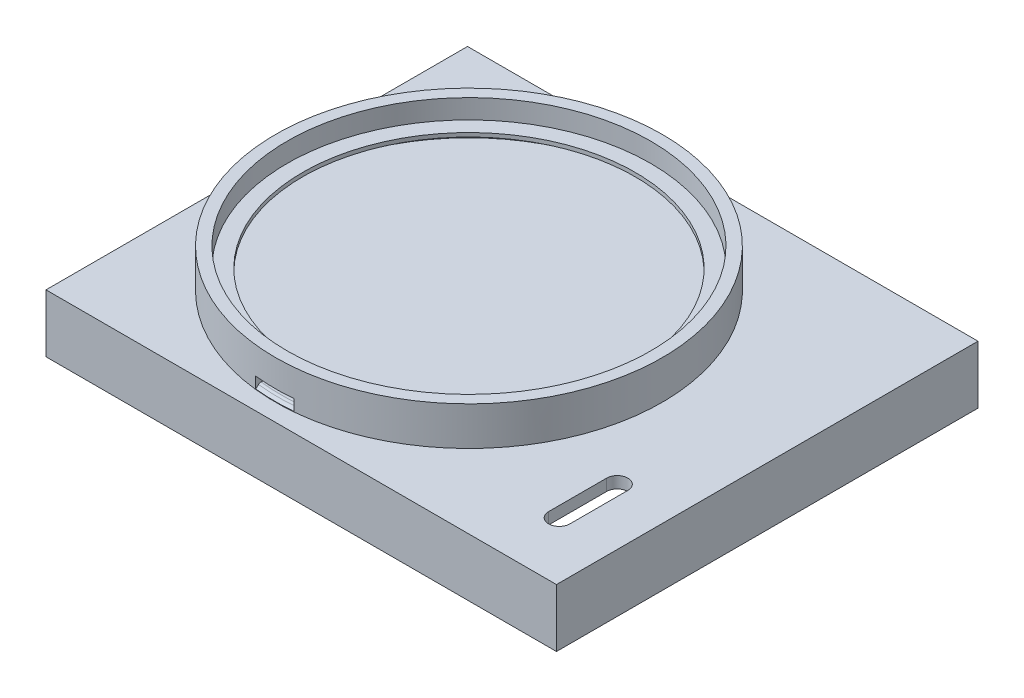
SolidWorks part; units mm, degrees
ref_plane "Front Plane" through (0, 0, 0) normal (0, 0, 1) x (1, 0, 0)
ref_plane "Top Plane" through (0, 0, 0) normal (0, 1, 0) x (1, 0, 0)
ref_plane "Right Plane" through (0, 0, 0) normal (1, 0, 0) x (0, 0, -1)
sketch "Sketch1" plane through (0, 0, 0) normal (0, 1, 0) x (1, 0, 0)
  line L1 (-66, -54.5) -> (66, -54.5)
  line L2 (-66, -54.5) -> (-66, 54.5)
  line L3 (-66, 54.5) -> (66, 54.5)
  line L4 (66, -54.5) -> (66, 54.5)
  line L5 (-66, -54.5) -> (66, 54.5) construction
  line L6 (-66, 54.5) -> (66, -54.5) construction
  point P0 (0, 0)
  dimension "D1" = 132
  dimension "D2" = 109
extrude "Boss-Extrude1" add sketch "Sketch1" along normal blind 15
sketch "Sketch2" plane through (0, 0, 0) normal (0, -1, 0) x (1, 0, 0)
  line L0 (-66, 54.5) -> (66, 54.5) construction
  line L1 (-63, -51.5) -> (63, -51.5)
  line L2 (-63, -51.5) -> (-63, 51.5)
  line L3 (-63, 51.5) -> (63, 51.5)
  line L4 (63, -51.5) -> (63, 51.5)
  line L5 (-63, -51.5) -> (63, 51.5) construction
  line L6 (-63, 51.5) -> (63, -51.5) construction
  line L7 (66, 54.5) -> (66, -54.5) construction
  point P0 (0, 0)
  dimension "D1" = 3
  dimension "D2" = 3
extrude "Cut-Extrude1" cut sketch "Sketch2" against normal blind 12
sketch "Sketch3" plane through (-63, 0, 0) normal (1, 0, 0) x (0, 0, -1)
  line L0 (-51.5, 0) -> (-51.5, 2) construction
  line L1 (-51.5, 0) -> (51.5, 0) construction
  line L2 (-51.5, 2) -> (51.5, 2) construction
  line L3 (51.5, 12) -> (51.5, 0) construction
  line L5 (-9, 1.25) -> (9, 1.25)
  line L6 (-9, 1.25) -> (-9, 2.75)
  line L7 (-9, 2.75) -> (9, 2.75)
  line L8 (9, 1.25) -> (9, 2.75)
  line L9 (-9, 1.25) -> (9, 2.75) construction
  line L10 (-9, 2.75) -> (9, 1.25) construction
  point P4 (0, 2)
  dimension "D1" = 2
  dimension "D2" = 18
  dimension "D3" = 1.5
sketch "Sketch6" plane through (63, 0, 0) normal (-1, 0, 0) x (0, 0, 1)
  line L0 (-51.5, 0) -> (-51.5, 2) construction
  line L1 (-51.5, 12) -> (-51.5, 0) construction
  line L2 (-51.5, 2) -> (51.5, 2) construction
  line L3 (51.5, 12) -> (51.5, 0) construction
  line L5 (-9, 2.75) -> (9, 2.75)
  line L6 (-9, 2.75) -> (-9, 1.25)
  line L7 (-9, 1.25) -> (9, 1.25)
  line L8 (9, 2.75) -> (9, 1.25)
  line L9 (-9, 2.75) -> (9, 1.25) construction
  line L10 (-9, 1.25) -> (9, 2.75) construction
  point P5 (0, 2)
  dimension "D1" = 2
  dimension "D2" = 18
  dimension "D3" = 1.5
extrude "Boss-Extrude6" add sketch "Sketch3" along normal blind 3
extrude "Boss-Extrude7" add sketch "Sketch6" along normal blind 3
sketch "Sketch14" plane through (0, 15, 0) normal (0, 1, 0) x (1, 0, 0)
  line L1 (48.6464, -24.1779) -> (54.1464, -24.1779) construction
  line L2 (48.6464, -24.1779) -> (48.6464, -39.1779)
  line L3 (48.6464, -39.1779) -> (54.1464, -39.1779) construction
  line L4 (54.1464, -24.1779) -> (54.1464, -39.1779)
  line L5 (48.6464, -24.1779) -> (54.1464, -39.1779) construction
  line L6 (48.6464, -39.1779) -> (54.1464, -24.1779) construction
  arc A0 (54.1464, -39.1779) -> (48.6464, -39.1779) centre (51.3964, -39.1779) cw
  arc A1 (54.1464, -24.1779) -> (48.6464, -24.1779) centre (51.3964, -24.1779) ccw
  point P0 (51.3964, -31.6779)
  dimension "D1" = 5.5
  dimension "D2" = 15
extrude "Cut-Extrude2" cut sketch "Sketch14" against normal blind 10
sketch "Sketch13" plane through (0, 15, 0) normal (0, 1, 0) x (1, 0, 0)
  line L0 (0, 0) -> (-11.1336, 0) construction
  line L1 (-66, 54.5) -> (66, -54.5) construction
  circle A0 centre (-11.1336, 0) radius 50
  dimension "D1" = 100
extrude "Boss-Extrude10" add sketch "Sketch13" along normal blind 4
sketch "Sketch15" [suppressed] plane through (0, 25, 0) normal (0, 1, 0) x (1, 0, 0)
  line L0 (-61.1336, 0) -> (38.8664, 0) construction
  circle A0 centre (-11.1336, 0) radius 50 construction
  circle A1 centre (-11.1336, 0) radius 50 construction
  circle A2 centre (-11.1336, 0) radius 47
  dimension "D1" = 94
  dimension "D2" = 3
extrude "Cut-Extrude3" [suppressed] cut sketch "Sketch15" against normal blind 7
sketch "Sketch16" [suppressed] plane through (0, 18, 0) normal (0, 1, 0) x (1, 0, 0)
  line L0 (-58.1336, 0) -> (35.8664, 0) construction
  circle A0 centre (-11.1336, 0) radius 47 construction
  circle A1 centre (-11.1336, 0) radius 47 construction
  circle A2 centre (-11.1336, 0) radius 43
  dimension "D1" = 86
  dimension "D2" = 4
sketch "Sketch18" plane through (0, 19, 0) normal (0, 1, 0) x (1, 0, 0)
  line L0 (-61.1336, 0) -> (38.8664, 0) construction
  circle A0 centre (-11.1336, 0) radius 50 construction
  circle A1 centre (-11.1336, 0) radius 50 construction
  circle A2 centre (-11.1336, 0) radius 47
  dimension "D1" = 3
extrude "Cut-Extrude6" cut sketch "Sketch18" against normal blind 3
ref_plane "Plane1" through (0, 19, 0) normal (0, 1, 0) x (1, 0, 0)
sketch "Sketch19" plane through (0, 19, 0) normal (0, 1, 0) x (1, 0, 0)
  circle A0 centre (-11.1336, 0) radius 50
extrude "Boss-Extrude11" add sketch "Sketch19" along normal blind 6
sketch "Sketch20" plane through (0, 25, 0) normal (0, 1, 0) x (1, 0, 0)
  line L0 (-61.1336, 0) -> (38.8664, 0) construction
  circle A0 centre (-11.1336, 0) radius 50 construction
  circle A1 centre (-11.1336, 0) radius 50 construction
  circle A2 centre (-11.1336, 0) radius 47
  dimension "D1" = 3
extrude "Cut-Extrude7" cut sketch "Sketch20" against normal blind 5
sketch "Sketch21" plane through (0, 20, 0) normal (0, 1, 0) x (1, 0, 0)
  line L0 (-58.1336, 0) -> (35.8664, 0) construction
  circle A0 centre (-11.1336, 0) radius 47 construction
  circle A1 centre (-11.1336, 0) radius 47 construction
  circle A2 centre (-11.1336, 0) radius 43
  dimension "D1" = 4
extrude "Cut-Extrude8" cut sketch "Sketch21" against normal blind 3
sketch "Sketch22" plane through (-66, 0, 0) normal (-1, 0, 0) x (0, 0, 1)
  line L0 (0, 25) -> (0, 15) construction
  line L1 (-5, 15.9919) -> (5, 15.9919)
  line L2 (-5, 15.9919) -> (-5, 17.9919)
  line L3 (-5, 17.9919) -> (5, 17.9919)
  line L4 (5, 15.9919) -> (5, 17.9919)
  line L5 (-5, 15.9919) -> (5, 17.9919) construction
  line L6 (-5, 17.9919) -> (5, 15.9919) construction
  line L7 (0, 15.9919) -> (0, 14.9919) construction
  point P0 (0, 16.9919)
  point P5 (0, 16.9919)
  dimension "D1" = 10
  dimension "D2" = 2
  dimension "D3" = 1
extrude "Cut-Extrude10" cut sketch "Sketch22" against normal blind 8.2
chamfer "Chamfer2" distance 1.3 angle 35 1 edges at (-61.1336, 15.9919, 0)
fillet "Fillet2" radius 1 1 edges at (-59.8336, 15.9919, 0)
sketch "Sketch23" plane through (0, 0, -54.5) normal (0, 0, -1) x (-1, 0, 0)
  line L0 (11.7213, 16) -> (11.7213, 15) construction
  line L1 (6.7213, 16) -> (16.7213, 16)
  line L2 (6.7213, 16) -> (6.7213, 18)
  line L3 (6.7213, 18) -> (16.7213, 18)
  line L4 (16.7213, 16) -> (16.7213, 18)
  line L5 (6.7213, 16) -> (16.7213, 18) construction
  line L6 (6.7213, 18) -> (16.7213, 16) construction
  line L7 (-66, 15) -> (66, 15) construction
  point P0 (11.7213, 17)
  point P9 (0, 0)
  point P10 (16.7213, 17)
  dimension "D1" = 10
  dimension "D2" = 2
  dimension "D3" = 1
extrude "Cut-Extrude11" cut sketch "Sketch23" against normal blind 8.2
chamfer "Chamfer3" distance 1 angle 41 1 edges at (-11.7242, 16, -49.9965)
fillet "Fillet3" radius 1 1 edges at (-11.7243, 16, -48.9964)
sketch "Sketch24" plane through (0, 0, 54.5) normal (0, 0, 1) x (1, 0, 0)
  line L0 (-11.5591, 16) -> (-11.5591, 15) construction
  line L1 (-16.5591, 16) -> (-6.5591, 16)
  line L2 (-16.5591, 16) -> (-16.5591, 18)
  line L3 (-16.5591, 18) -> (-6.5591, 18)
  line L4 (-6.5591, 16) -> (-6.5591, 18)
  line L5 (-16.5591, 16) -> (-6.5591, 18) construction
  line L6 (-16.5591, 18) -> (-6.5591, 16) construction
  line L7 (-66, 15) -> (66, 15) construction
  point P0 (-11.5591, 17)
  point P9 (-12.2356, 17)
  point P10 (-11.5591, 17)
  dimension "D1" = 10
  dimension "D2" = 2
  dimension "D3" = 1
extrude "Cut-Extrude12" cut sketch "Sketch24" against normal blind 8.2
chamfer "Chamfer4" distance 1 angle 41 1 edges at (-11.5612, 16, 49.9982)
fillet "Fillet4" radius 1 1 edges at (-11.5613, 16, 48.9981)
